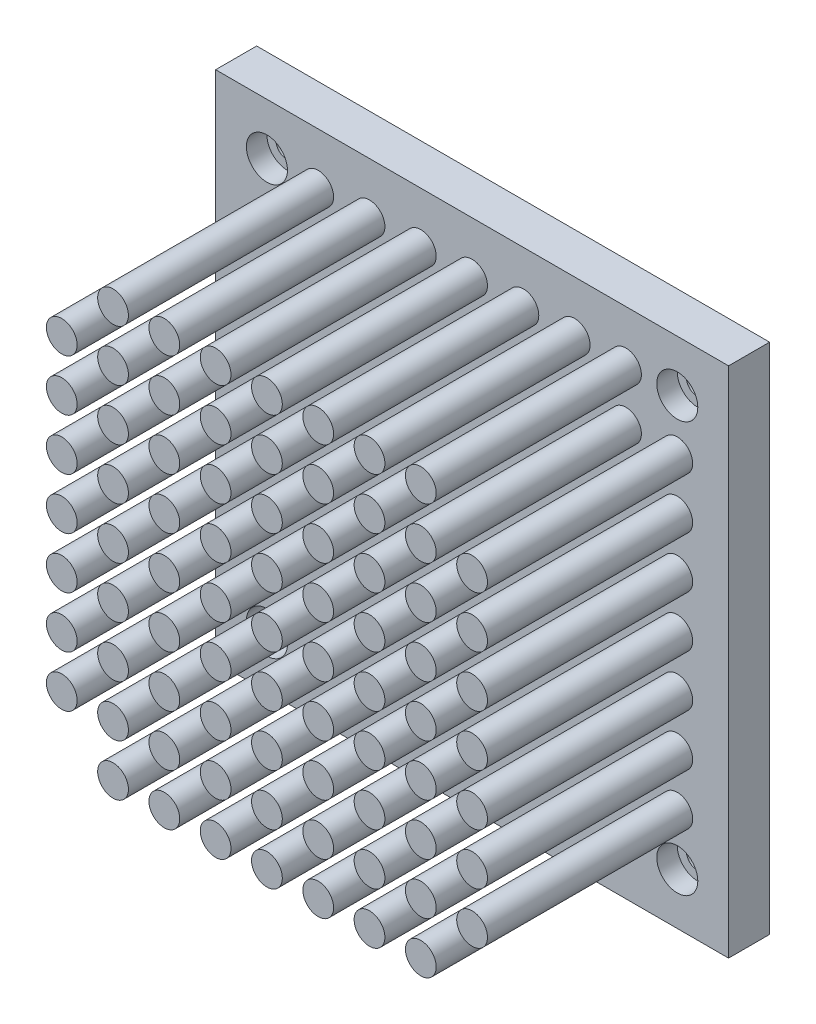
SolidWorks part; units mm, degrees
ref_plane "前视基准面" through (0, 0, 0) normal (0, 0, 1) x (1, 0, 0)
ref_plane "上视基准面" through (0, 0, 0) normal (0, 1, 0) x (1, 0, 0)
ref_plane "右视基准面" through (0, 0, 0) normal (1, 0, 0) x (0, 0, -1)
sketch "草图1" plane through (0, 0, 0) normal (0, 0, 1) x (1, 0, 0)
  line L0 (-50, -50) -> (50, -50)
  line L1 (50, -50) -> (50, 50)
  line L2 (50, 50) -> (-50, 50)
  line L3 (-50, 50) -> (-50, -50)
extrude "凸台-拉伸1" add sketch "草图1" along normal blind 8
sketch "草图2" plane through (0, 0, 0) normal (0, 0, 1) x (1, 0, 0)
  line L0 (-30, -30) -> (30, -30)
  line L1 (30, -30) -> (30, 30)
  line L2 (30, 30) -> (-30, 30)
  line L3 (-30, 30) -> (-30, -30)
extrude "凸台-拉伸2" add sketch "草图2" against normal blind 2
ref_plane "基准面1" through (0, 0, 8) normal (0, 0, 1) x (1, 0, 0)
sketch "草图3" plane through (0, 0, 8) normal (0, 0, 1) x (1, 0, 0)
  circle A0 centre (-40, -30) radius 3
  circle A1 centre (-40, -20) radius 3
  circle A2 centre (-40, -10) radius 3
  circle A3 centre (-40, 0) radius 3
  circle A4 centre (-40, 10) radius 3
  circle A5 centre (-40, 20) radius 3
  circle A6 centre (-40, 30) radius 3
  circle A7 centre (-30, -40) radius 3
  circle A8 centre (-30, -30) radius 3
  circle A9 centre (-30, -20) radius 3
  circle A10 centre (-30, -10) radius 3
  circle A11 centre (-30, 0) radius 3
  circle A12 centre (-30, 10) radius 3
  circle A13 centre (-30, 20) radius 3
  circle A14 centre (-30, 30) radius 3
  circle A15 centre (-30, 40) radius 3
  circle A16 centre (-20, -40) radius 3
  circle A17 centre (-20, -30) radius 3
  circle A18 centre (-20, -20) radius 3
  circle A19 centre (-20, -10) radius 3
  circle A20 centre (-20, 0) radius 3
  circle A21 centre (-20, 10) radius 3
  circle A22 centre (-20, 20) radius 3
  circle A23 centre (-20, 30) radius 3
  circle A24 centre (-20, 40) radius 3
  circle A25 centre (-10, -40) radius 3
  circle A26 centre (-10, -30) radius 3
  circle A27 centre (-10, -20) radius 3
  circle A28 centre (-10, -10) radius 3
  circle A29 centre (-10, 0) radius 3
  circle A30 centre (-10, 10) radius 3
  circle A31 centre (-10, 20) radius 3
  circle A32 centre (-10, 30) radius 3
  circle A33 centre (-10, 40) radius 3
  circle A34 centre (0, -40) radius 3
  circle A35 centre (0, -30) radius 3
  circle A36 centre (0, -20) radius 3
  circle A37 centre (0, -10) radius 3
  circle A38 centre (0, 0) radius 3
  circle A39 centre (0, 10) radius 3
  circle A40 centre (0, 20) radius 3
  circle A41 centre (0, 30) radius 3
  circle A42 centre (0, 40) radius 3
  circle A43 centre (10, -40) radius 3
  circle A44 centre (10, -30) radius 3
  circle A45 centre (10, -20) radius 3
  circle A46 centre (10, -10) radius 3
  circle A47 centre (10, 0) radius 3
  circle A48 centre (10, 10) radius 3
  circle A49 centre (10, 20) radius 3
  circle A50 centre (10, 30) radius 3
  circle A51 centre (10, 40) radius 3
  circle A52 centre (20, -40) radius 3
  circle A53 centre (20, -30) radius 3
  circle A54 centre (20, -20) radius 3
  circle A55 centre (20, -10) radius 3
  circle A56 centre (20, 0) radius 3
  circle A57 centre (20, 10) radius 3
  circle A58 centre (20, 20) radius 3
  circle A59 centre (20, 30) radius 3
  circle A60 centre (20, 40) radius 3
  circle A61 centre (30, -40) radius 3
  circle A62 centre (30, -30) radius 3
  circle A63 centre (30, -20) radius 3
  circle A64 centre (30, -10) radius 3
  circle A65 centre (30, 0) radius 3
  circle A66 centre (30, 10) radius 3
  circle A67 centre (30, 20) radius 3
  circle A68 centre (30, 30) radius 3
  circle A69 centre (30, 40) radius 3
  circle A70 centre (40, -30) radius 3
  circle A71 centre (40, -20) radius 3
  circle A72 centre (40, -10) radius 3
  circle A73 centre (40, 0) radius 3
  circle A74 centre (40, 10) radius 3
  circle A75 centre (40, 20) radius 3
  circle A76 centre (40, 30) radius 3
extrude "凸台-拉伸3" add sketch "草图3" along normal blind 40
sketch "草图4" plane through (0, 0, 8) normal (0, 0, 1) x (1, 0, 0)
  circle A0 centre (-40, -40) radius 4
  circle A1 centre (-40, 40) radius 4
  circle A2 centre (40, -40) radius 4
  circle A3 centre (40, 40) radius 4
extrude "切除-拉伸1" cut sketch "草图4" against normal blind 4
sketch "草图5" plane through (0, 0, 8) normal (0, 0, 1) x (1, 0, 0)
  circle A0 centre (-40, -40) radius 2.25
  circle A1 centre (-40, 40) radius 2.25
  circle A2 centre (40, -40) radius 2.25
  circle A3 centre (40, 40) radius 2.25
extrude "切除-拉伸2" cut sketch "草图5" against normal through all
